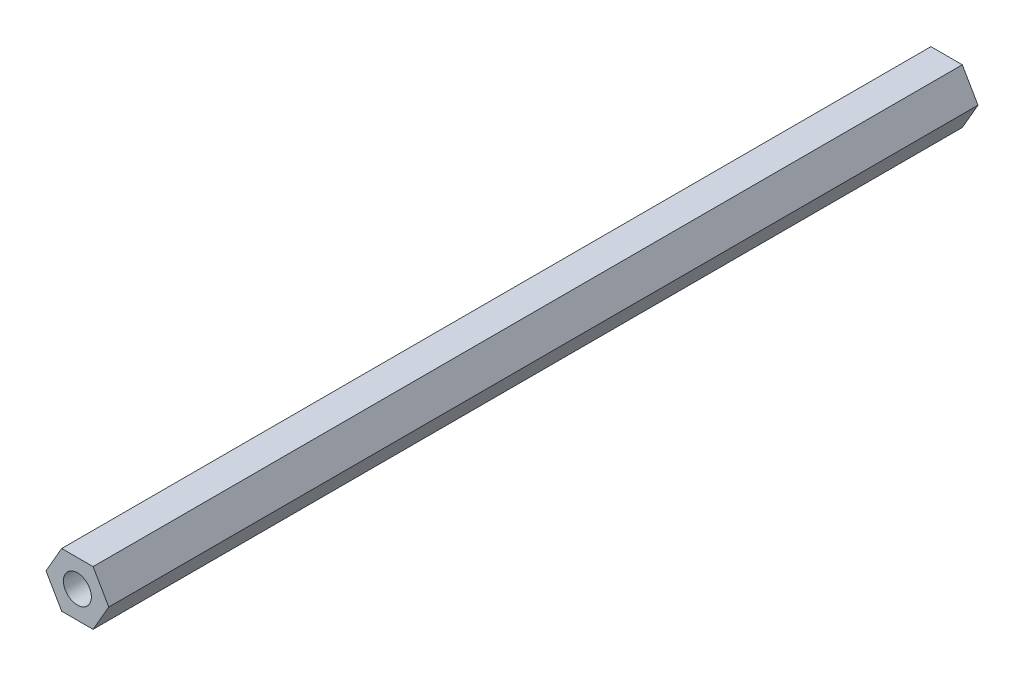
SolidWorks part; units mm, degrees
ref_plane "Front Plane" through (0, 0, 0) normal (0, 0, 1) x (1, 0, 0)
ref_plane "Top Plane" through (0, 0, 0) normal (0, 1, 0) x (1, 0, 0)
ref_plane "Right Plane" through (0, 0, 0) normal (1, 0, 0) x (0, 0, -1)
sketch "Sketch1" plane through (0, 0, 0) normal (0, 0, 1) x (1, 0, 0)
  line L1 (-7.3323, 0) -> (-3.6662, -6.35)
  line L2 (-3.6662, -6.35) -> (3.6662, -6.35)
  line L3 (3.6662, -6.35) -> (7.3323, 0)
  line L4 (7.3323, 0) -> (3.6662, 6.35)
  line L5 (3.6662, 6.35) -> (-3.6662, 6.35)
  line L6 (-3.6662, 6.35) -> (-7.3323, 0)
  circle A0 centre (0, 0) radius 6.35 construction
  circle A1 centre (0, 0) radius 3.2639
  dimension "D1" = 12.7
  dimension "D2" = 6.5278
extrude "Boss-Extrude1" add sketch "Sketch1" along normal blind 203.073
